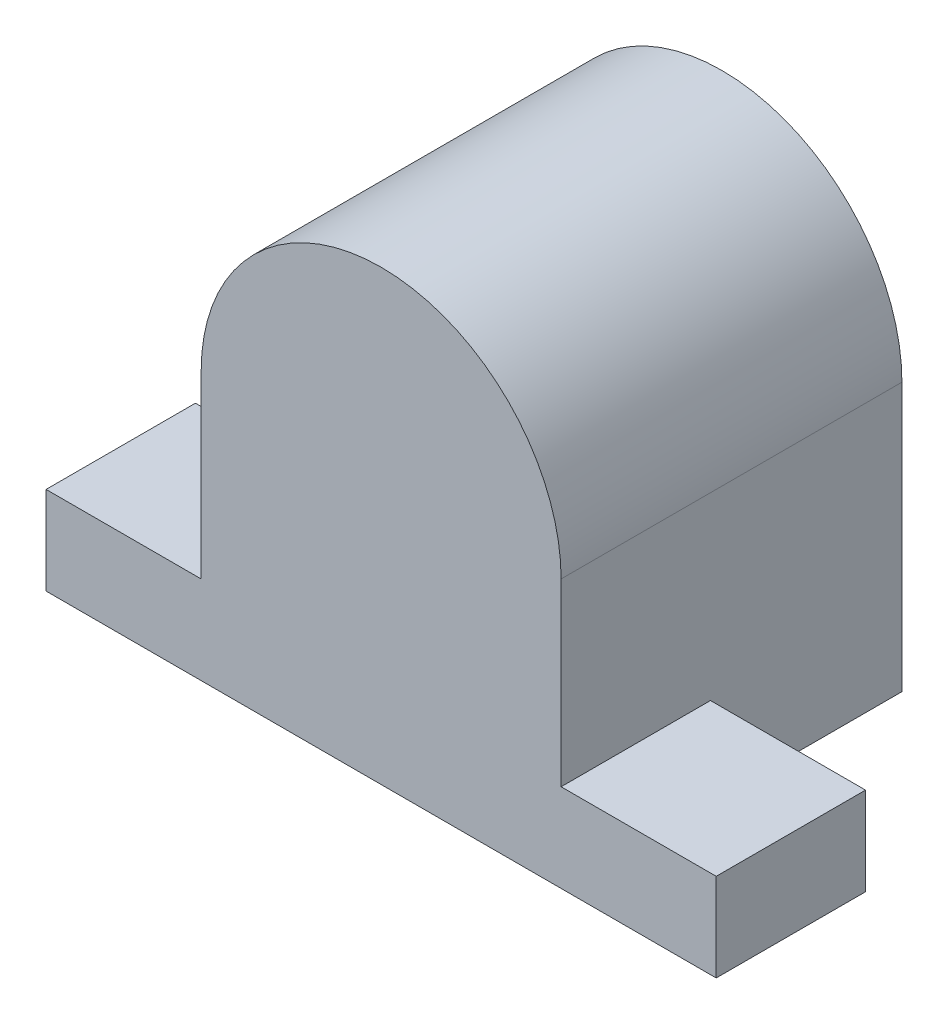
SolidWorks part; units mm, degrees
ref_plane "Front Plane" through (0, 0, 0) normal (0, 0, 1) x (1, 0, 0)
ref_plane "Top Plane" through (0, 0, 0) normal (0, 1, 0) x (1, 0, 0)
ref_plane "Right Plane" through (0, 0, 0) normal (1, 0, 0) x (0, 0, -1)
sketch "Sketch1" plane through (0, 0, 0) normal (0, 0, 1) x (1, 0, 0)
  line L0 (11.938, 0) -> (11.938, -11.938)
  line L1 (11.938, -11.938) -> (22.225, -11.938)
  line L2 (22.225, -11.938) -> (22.225, -17.78)
  line L3 (22.225, -17.78) -> (-22.225, -17.78)
  line L4 (-22.225, -17.78) -> (-22.225, -11.938)
  line L5 (-22.225, -11.938) -> (-11.938, -11.938)
  line L6 (-11.938, -11.938) -> (-11.938, 0)
  line L7 (0, 0) -> (0, -32.5713) construction
  circle A0 centre (0, 0) radius 8.763
  arc A1 (11.938, 0) -> (-11.938, 0) centre (0, 0) ccw
  dimension "D1" = 17.526
  dimension "D2" = 3.175
  dimension "D3" = 17.78
  dimension "D4" = 44.45
extrude "Boss-Extrude1" add sketch "Sketch1" along normal blind 3.556
sketch "Sketch2" plane through (0, 0, 3.556) normal (0, 0, 1) x (1, 0, 0)
  line L7 (-11.938, 0) -> (-11.938, -11.938)
  line L8 (-11.938, -11.938) -> (-22.225, -11.938)
  line L9 (-22.225, -11.938) -> (-22.225, -17.78)
  line L10 (-22.225, -17.78) -> (22.225, -17.78)
  line L11 (22.225, -17.78) -> (22.225, -11.938)
  line L12 (22.225, -11.938) -> (11.938, -11.938)
  line L13 (11.938, -11.938) -> (11.938, 0)
  line L14 (-11.938, 0) -> (-11.938, -11.938)
  line L15 (-11.938, -11.938) -> (-22.225, -11.938)
  line L16 (-22.225, -11.938) -> (-22.225, -17.78)
  line L17 (-22.225, -17.78) -> (22.225, -17.78)
  line L18 (22.225, -17.78) -> (22.225, -11.938)
  line L19 (22.225, -11.938) -> (11.938, -11.938)
  line L20 (11.938, -11.938) -> (11.938, 0)
  arc A1 (11.938, 0) -> (-11.938, 0) centre (0, 0) ccw
  arc A2 (11.938, 0) -> (-11.938, 0) centre (0, 0) ccw
  dimension "D1" = 0
extrude "Boss-Extrude2" add sketch "Sketch2" along normal blind 6.35
sketch "Sketch3" plane through (0, 0, 0) normal (0, 0, -1) x (-1, 0, 0)
  circle A0 centre (0, 0) radius 11.938
  arc A1 (11.938, 0) -> (-11.938, 0) centre (0, 0) ccw construction
  circle A2 centre (0, 0) radius 8.763 construction
  circle A3 centre (0, 0) radius 8.763
extrude "Boss-Extrude3" add sketch "Sketch3" along normal blind 12.7
sketch "Sketch4" plane through (0, 0, 3.556) normal (0, 0, -1) x (-1, 0, 0)
  circle A1 centre (0, 0) radius 8.763
  circle A2 centre (0, 0) radius 8.763
  dimension "D1" = 0
extrude "Boss-Extrude4" add sketch "Sketch4" along normal blind 12.7
sketch "Sketch5" plane through (0, 0, 0) normal (0, 0, -1) x (-1, 0, 0)
  line L0 (-11.938, 0) -> (-11.938, -17.78)
  line L1 (22.225, -17.78) -> (-22.225, -17.78) construction
  line L2 (-11.938, -17.78) -> (11.938, -17.78)
  line L3 (11.938, -17.78) -> (11.938, 0)
  circle A0 centre (0, 0) radius 11.938 construction
  arc A1 (-11.938, 0) -> (11.938, 0) centre (0, 0) ccw
extrude "Boss-Extrude5" add sketch "Sketch5" along normal blind 12.7
